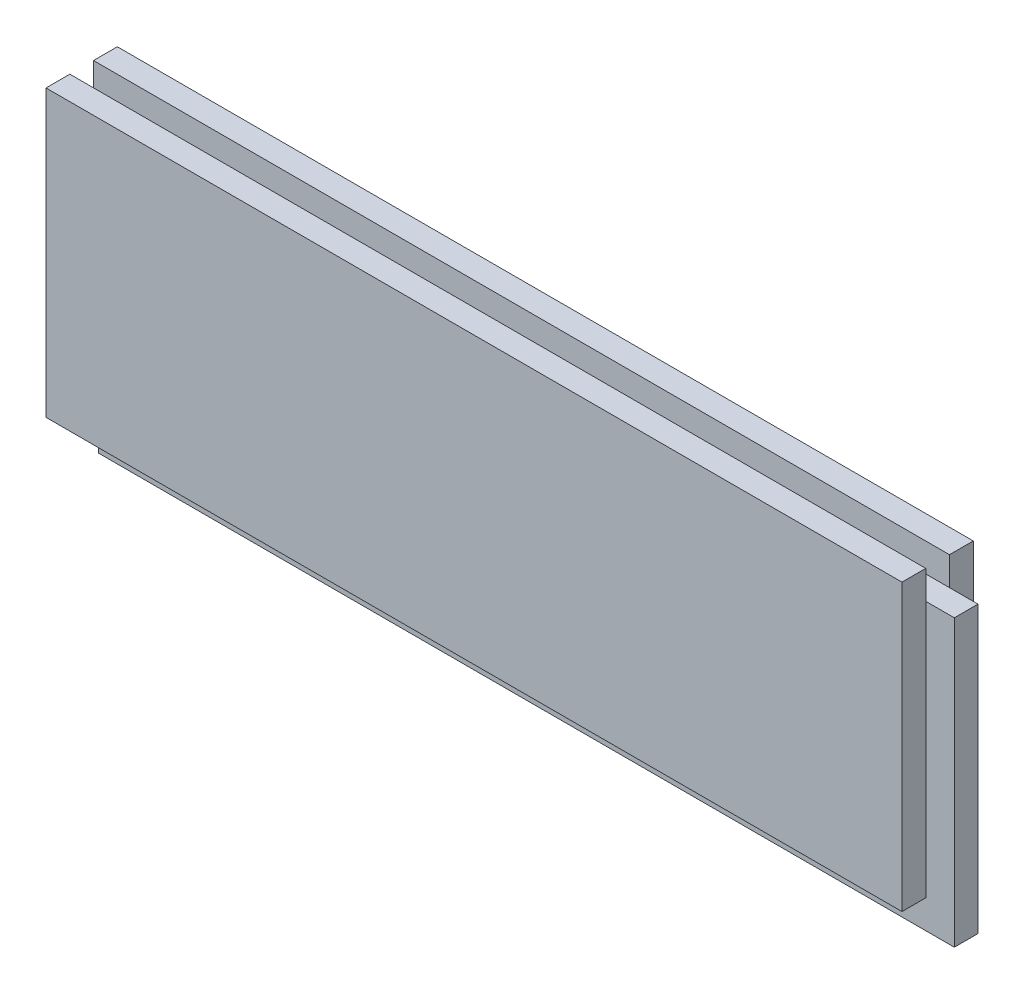
SolidWorks part; units mm, degrees
ref_plane "Front Plane" through (0, 0, 0) normal (0, 0, 1) x (1, 0, 0)
ref_plane "Top Plane" through (0, 0, 0) normal (0, 1, 0) x (1, 0, 0)
ref_plane "Right Plane" through (0, 0, 0) normal (1, 0, 0) x (0, 0, -1)
sketch "Sketch1" plane through (0, 0, 0) normal (0, 0, 1) x (1, 0, 0)
  line L1 (30, -10) -> (-30, -10)
  line L2 (30, -10) -> (30, 10)
  line L3 (30, 10) -> (-30, 10)
  line L4 (-30, -10) -> (-30, 10)
  line L5 (30, -10) -> (-30, 10) construction
  line L6 (30, 10) -> (-30, -10) construction
  point P0 (0, 0)
  dimension "D1" = 20
  dimension "D2" = 60
extrude "Boss-Extrude1" add sketch "Sketch1" along normal mid plane 5
sketch "Sketch2" plane through (0, 10, 0) normal (0, 1, 0) x (1, 0, 0)
  line L0 (-30, -2.5) -> (-30, 2.5) construction
  line L1 (-30, 0.83) -> (30, 0.83)
  line L2 (-30, 0.83) -> (-30, -0.83)
  line L3 (-30, -0.83) -> (30, -0.83)
  line L4 (30, 0.83) -> (30, -0.83)
  line L5 (30, -2.5) -> (30, 2.5) construction
  line L6 (0, 0.83) -> (0, -0.83) construction
  point P11 (0, 0)
  point P12 (0, 0)
  dimension "D1" = 1.66
extrude "Cut-Extrude1" cut sketch "Sketch2" against normal blind 2
sketch "Sketch3" plane through (-30, 0, 0) normal (-1, 0, 0) x (0, 0, 1)
  line L0 (2.5, -10) -> (-2.5, -10) construction
  line L1 (-0.83, 8) -> (0.83, 8)
  line L2 (-0.83, 8) -> (-0.83, -10)
  line L3 (-0.83, -10) -> (0.83, -10)
  line L4 (0.83, 8) -> (0.83, -10)
  line L5 (0.83, 8) -> (0.83, 10) construction
extrude "Cut-Extrude2" cut sketch "Sketch3" against normal blind 2
sketch "Sketch4" plane through (0, -10, 0) normal (0, -1, 0) x (1, 0, 0)
  line L0 (30, 2.5) -> (30, -2.5) construction
  line L1 (-28, 0.83) -> (30, 0.83)
  line L2 (-28, 0.83) -> (-28, -0.83)
  line L3 (-28, -0.83) -> (30, -0.83)
  line L4 (30, 0.83) -> (30, -0.83)
  line L5 (-28, -0.83) -> (-30, -0.83) construction
extrude "Boss-Extrude2" add sketch "Sketch4" along normal blind 2
sketch "Sketch5" plane through (30, 0, 0) normal (1, 0, 0) x (0, 0, -1)
  line L1 (-0.83, -12) -> (0.83, -12)
  line L2 (-0.83, -12) -> (-0.83, 8)
  line L3 (-0.83, 8) -> (0.83, 8)
  line L4 (0.83, -12) -> (0.83, 8)
extrude "Boss-Extrude3" add sketch "Sketch5" along normal blind 2
